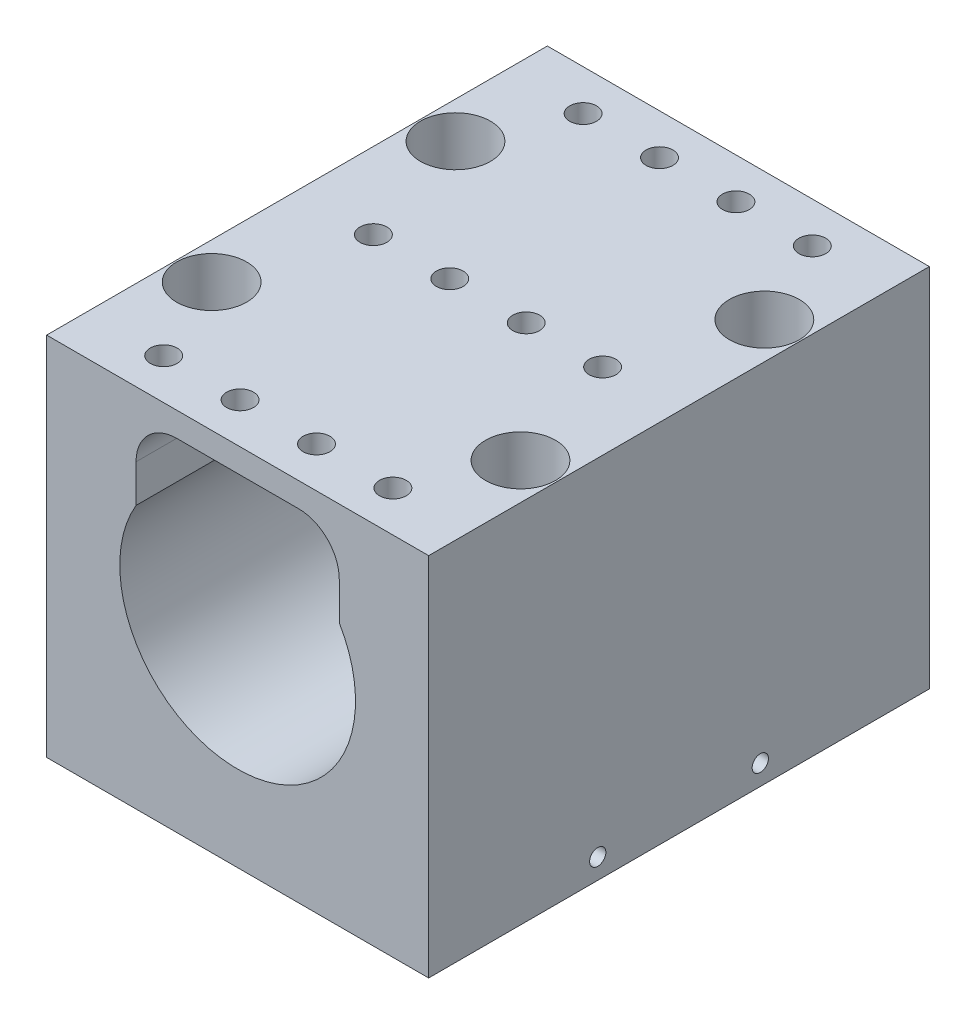
SolidWorks part; units mm, degrees
material "6061 Сплав"
ref_plane "Front" through (0, 0, 0) normal (0, 0, 1) x (1, 0, 0)
ref_plane "Top" through (0, 0, 0) normal (0, 1, 0) x (1, 0, 0)
ref_plane "Right" through (0, 0, 0) normal (1, 0, 0) x (0, 0, -1)
sketch "Эскиз1" plane through (0, 0, 0) normal (0, 0, 1) x (1, 0, 0)
  line L1 (-23.5, 22.5) -> (23.5, 22.5)
  line L2 (-23.5, 22.5) -> (-23.5, -22.5)
  line L3 (-23.5, -22.5) -> (23.5, -22.5)
  line L4 (23.5, 22.5) -> (23.5, -22.5)
  line L5 (-23.5, 22.5) -> (23.5, -22.5) construction
  line L6 (-23.5, -22.5) -> (23.5, 22.5) construction
  point P0 (0, 0)
  dimension "D1" = 47
  dimension "D2" = 45
extrude "Бобышка-Вытянуть1" add sketch "Эскиз1" along normal blind 61.6
sketch "Эскиз2" plane through (0, 0, 61.6) normal (0, 0, 1) x (1, 0, 0)
  line L0 (23.5, 22.5) -> (-23.5, 22.5) construction
  circle A0 centre (0, 2.5) radius 14.5
  dimension "D1" = 20
extrude "Вырез-Вытянуть1" cut sketch "Эскиз2" against normal blind 100
sketch "Эскиз6" plane through (0, 0, 0) normal (0, 0, -1) x (-1, 0, 0)
  line L0 (0, 2.5) -> (-29.6357, 19.6102) construction
  line L1 (0, 2.5) -> (-30.2795, -14.9819) construction
  line L2 (0, 2.5) -> (27.1514, 18.1759) construction
  line L3 (0, 2.5) -> (31.0307, -15.4156) construction
  line L4 (0, 2.5) -> (-35.9537, 2.5) construction
  line L6 (-23.5, 22.5) -> (23.5, 22.5) construction
  circle A1 centre (-16.8875, 12.25) radius 2.1
  circle A2 centre (-16.8875, -7.25) radius 2.1
  circle A3 centre (16.8875, 12.25) radius 2.1
  circle A4 centre (16.8875, -7.25) radius 2.1
  dimension "D1" = 30
  dimension "D5" = 19.5
  dimension "D2" = 30
  dimension "D3" = 120
  dimension "D4" = 60
  dimension "D6" = 19.5
  dimension "D7" = 10.25
  dimension "D8" = 10.25
extrude "Вырез-Вытянуть5" cut sketch "Эскиз6" against normal blind 15
sketch "Эскиз7" plane through (0, 0, 0) normal (0, 0, -1) x (-1, 0, 0)
  line L0 (-23.5, 22.5) -> (23.5, 22.5) construction
  line L1 (-12.5, 19.5) -> (12.5, 19.5)
  line L2 (-12.5, 19.5) -> (-12.5, 9.8485)
  line L3 (-12.5, 9.8485) -> (12.5, 9.8485)
  line L4 (12.5, 19.5) -> (12.5, 9.8485)
  line L6 (-23.5, -22.5) -> (-23.5, 22.5) construction
  circle A0 centre (0, 2.5) radius 14.5 construction
  dimension "D1" = 25
  dimension "D2" = 3
  dimension "D3" = 11
extrude "Вырез-Вытянуть6" cut sketch "Эскиз7" against normal blind 100
fillet "Скругление1" radius 5 2 edges at (12.5, 19.5, 30.8) (-12.5, 19.5, 30.8)
sketch "Эскиз10" plane through (0, 22.5, 0) normal (0, 1, 0) x (1, 0, 0)
  line L1 (23.5, 0) -> (-23.5, 0) construction
  line L2 (-23.5, -61.6) -> (-23.5, 0) construction
  circle A0 centre (-19, -15.8) radius 2.75
  dimension "D1" = 15.8
  dimension "D2" = 4.5
extrude "Вырез-Вытянуть8" cut sketch "Эскиз10" against normal blind 100
pattern_linear "Линейный массив2" count 2 spacing 38 along (1, 0, 0) count 2 spacing 30 along (0, 0, 1) of "Вырез-Вытянуть8"
sketch "Эскиз11" plane through (0, 22.5, 0) normal (0, 1, 0) x (1, 0, 0)
  circle A0 centre (-19, -15.8) radius 4.3
extrude "Вырез-Вытянуть9" cut sketch "Эскиз11" against normal blind 40
pattern_linear "Линейный массив3" count 2 spacing 38 along (1, 0, 0) count 2 spacing 30 along (0, 0, 1) of "Вырез-Вытянуть9"
sketch "Эскиз12" plane through (0, 22.5, 0) normal (0, 1, 0) x (1, 0, 0)
  line L0 (-23.5, -61.6) -> (-23.5, 0) construction
  line L1 (23.5, 0) -> (-23.5, 0) construction
  circle A0 centre (-14.1, -5) radius 1.65
  dimension "D1" = 9.4
  dimension "D2" = 5
extrude "Вырез-Вытянуть10" cut sketch "Эскиз12" against normal blind 5
pattern_linear "Линейный массив4" count 4 spacing 9.4 along (1, 0, 0) of "Вырез-Вытянуть10"
pattern_linear "Линейный массив5" count 2 spacing 25.8 along (0, 0, 1) of "Линейный массив4", "Вырез-Вытянуть10"
pattern_linear "Линейный массив6" count 2 spacing 51.6 along (0, 0, 1) of "Линейный массив4", "Вырез-Вытянуть10"
sketch "Эскиз13" plane through (23.5, 0, 0) normal (1, 0, 0) x (0, 0, -1)
  line L0 (-61.6, -22.5) -> (0, -22.5) construction
  line L1 (-61.6, -22.5) -> (-61.6, 22.5) construction
  circle A0 centre (-40.8, -20) radius 1
  circle A1 centre (-20.8, -20) radius 1
  dimension "D1" = 2.5
  dimension "D2" = 2.5
  dimension "D3" = 20
  dimension "D4" = 20.8
extrude "Вырез-Вытянуть11" cut sketch "Эскиз13" against normal blind 100
